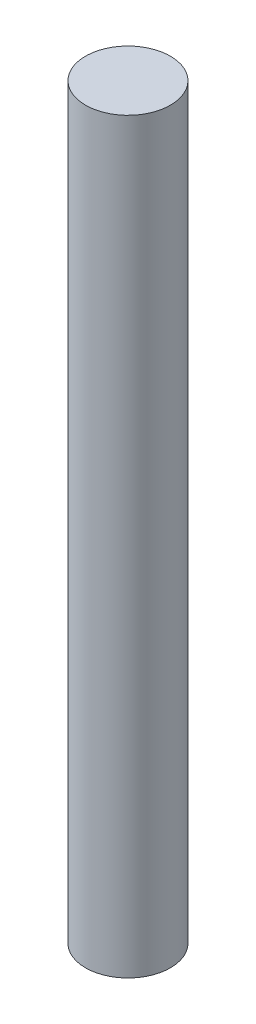
SolidWorks part; units mm, degrees
ref_plane "Front" through (0, 0, 0) normal (0, 0, 1) x (1, 0, 0)
ref_plane "Top" through (0, 0, 0) normal (0, 1, 0) x (1, 0, 0)
ref_plane "Right" through (0, 0, 0) normal (1, 0, 0) x (0, 0, -1)
sketch "Sketch1" plane through (0, 0, 0) normal (0, 1, 0) x (1, 0, 0)
  circle A0 centre (0, 0) radius 1.25
  dimension "D1" = 2.5
extrude "Boss-Extrude1" add sketch "Sketch1" along normal blind 22
